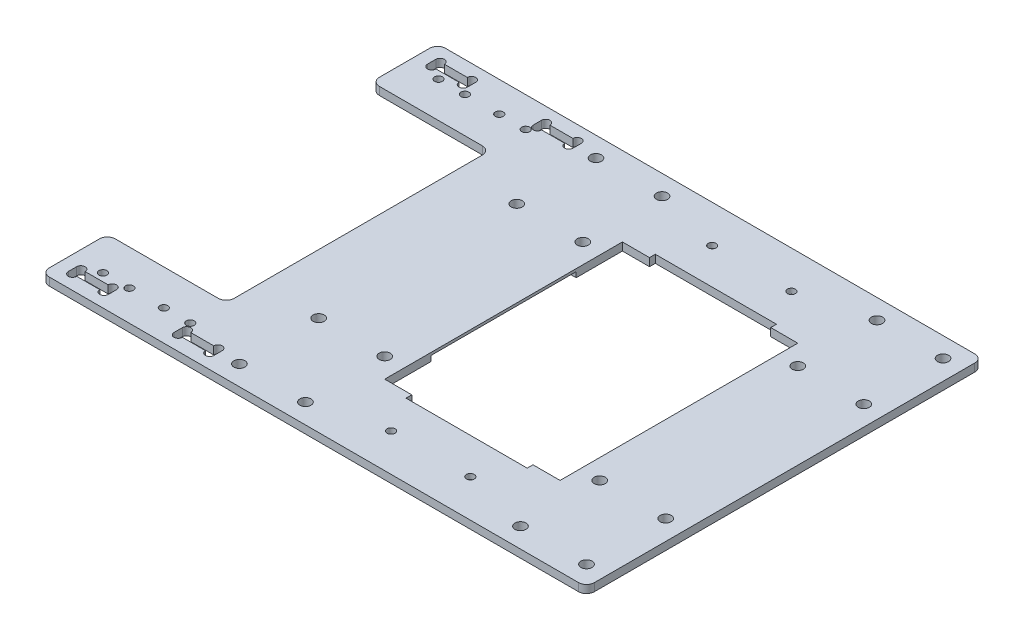
SolidWorks part; units mm, degrees
material "Thornel Mat VMA"
ref_plane "前视基准面" through (0, 0, 0) normal (0, 0, 1) x (1, 0, 0)
ref_plane "上视基准面" through (0, 0, 0) normal (0, 1, 0) x (1, 0, 0)
ref_plane "右视基准面" through (0, 0, 0) normal (1, 0, 0) x (0, 0, -1)
other "Configuration Table"
sketch "草图1" plane through (0, 0, 0) normal (0, 1, 0) x (1, 0, 0)
  line L0 (0, 0) -> (0, 27.529) construction
  line L1 (0, 0) -> (24.492, 0) construction
  line L2 (-73.2, 75) -> (-73.2, -75) construction
  line L3 (-133.2, -75) -> (73.2, -75)
  line L4 (-133.2, -75) -> (-133.2, 75)
  line L5 (-133.2, 75) -> (73.2, 75)
  line L6 (73.2, -75) -> (73.2, 75)
  line L7 (-133.2, -75) -> (73.2, 75) construction
  line L8 (-133.2, 75) -> (73.2, -75) construction
  circle A0 centre (65.7, 67.5) radius 2.1
  circle A1 centre (65.7, -67.5) radius 2.1
  circle A2 centre (-65.7, -67.5) radius 2.1
  circle A3 centre (-65.7, 67.5) radius 2.1
  circle A4 centre (-65.7, 37.5) radius 2.1 construction
  circle A5 centre (-40.7, 37.5) radius 2.1 construction
  circle A6 centre (-40.7, 67.5) radius 2.1 construction
  circle A7 centre (-40.7, -67.5) radius 2.1 construction
  circle A8 centre (-40.7, -37.5) radius 2.1 construction
  circle A9 centre (-65.7, -37.5) radius 2.1 construction
  circle A10 centre (40.7, -67.5) radius 2.1 construction
  circle A11 centre (40.7, -37.5) radius 2.1 construction
  circle A12 centre (65.7, -37.5) radius 2.1 construction
  circle A13 centre (65.7, 37.5) radius 2.1 construction
  circle A14 centre (40.7, 37.5) radius 2.1 construction
  circle A15 centre (40.7, 67.5) radius 2.1 construction
  circle A16 centre (-65.7, 37.5) radius 2.1
  circle A17 centre (-40.7, 37.5) radius 2.1
  circle A18 centre (-40.7, 67.5) radius 2.1
  circle A19 centre (-40.7, -67.5) radius 2.1
  circle A20 centre (-40.7, -37.5) radius 2.1
  circle A21 centre (-65.7, -37.5) radius 2.1
  circle A22 centre (40.7, -67.5) radius 2.1
  circle A23 centre (40.7, -37.5) radius 2.1
  circle A24 centre (65.7, -37.5) radius 2.1
  circle A25 centre (65.7, 37.5) radius 2.1
  circle A26 centre (40.7, 37.5) radius 2.1
  circle A27 centre (40.7, 67.5) radius 2.1
  circle A29 centre (-98.4, 63.575) radius 1.5
  circle A30 centre (-98.4, 63.575) radius 1.5
  circle A31 centre (-88.4, 63.575) radius 1.5
  circle A32 centre (-88.4, 63.575) radius 1.5
  circle A33 centre (-111.4, 63.575) radius 1.5
  circle A34 centre (-111.4, 63.575) radius 1.5
  circle A35 centre (-121.4, 63.575) radius 1.5
  circle A36 centre (-121.4, 63.575) radius 1.5
  circle A37 centre (-121.4, -63.475) radius 1.5
  circle A38 centre (-121.4, -63.475) radius 1.5
  circle A39 centre (-111.4, -63.475) radius 1.5
  circle A40 centre (-111.4, -63.475) radius 1.5
  circle A41 centre (-98.4, -63.425) radius 1.5
  circle A42 centre (-98.4, -63.425) radius 1.5
  circle A43 centre (-88.4, -63.425) radius 1.5
  circle A44 centre (-88.4, -63.425) radius 1.5
  point P6 (-30, 0)
  dimension "D1" = 135
  dimension "D2" = 131.4
  dimension "D3" = 4.2
  dimension "D4" = 7.5
  dimension "D5" = 7.5
  dimension "D6" = 60
  dimension "D7" = 7.5
  dimension "D8" = 0
  dimension "D9" = 0
  dimension "D10" = 0
  dimension "D11" = 0
  dimension "D12" = 0
  dimension "D13" = 0
  dimension "D14" = 0
  dimension "D15" = 0
extrude "凸台-拉伸1" add sketch "草图1" along normal blind 3
sketch "草图2" plane through (0, 0, 0) normal (0, 1, 0) x (1, 0, 0)
  line L0 (-128.4, -68) -> (-113.3, -68) construction
  line L1 (-125.2, -66.425) -> (-116.5, -66.425)
  line L2 (-128.4, -66.425) -> (-128.4, -69.575)
  line L3 (-125.2, -69.575) -> (-116.5, -69.575)
  line L4 (-113.3, -66.425) -> (-113.3, -69.575)
  line L5 (-120.85, -69.575) -> (-120.85, -66.425) construction
  line L6 (-85.2, -66.425) -> (-76.5, -66.425)
  line L7 (-88.4, -66.425) -> (-88.4, -69.575)
  line L8 (-85.2, -69.575) -> (-76.5, -69.575)
  line L9 (-73.3, -66.425) -> (-73.3, -69.575)
  line L10 (-88.4, -68) -> (-73.3, -68) construction
  line L11 (-80.85, -69.575) -> (-80.85, -66.425) construction
  line L12 (-133.2, 75) -> (-133.2, -75) construction
  line L14 (-133.2, 0) -> (73.2, 0) construction
  line L15 (73.2, -75) -> (73.2, 75) construction
  line L16 (-80.85, 69.575) -> (-80.85, 66.425) construction
  line L17 (-88.4, 68) -> (-73.3, 68) construction
  line L18 (-120.85, 69.575) -> (-120.85, 66.425) construction
  line L19 (-128.4, 68) -> (-113.3, 68) construction
  line L20 (-73.3, 66.425) -> (-73.3, 69.575)
  line L21 (-85.2, 69.575) -> (-76.5, 69.575)
  line L22 (-88.4, 66.425) -> (-88.4, 69.575)
  line L23 (-85.2, 66.425) -> (-76.5, 66.425)
  line L24 (-113.3, 66.425) -> (-113.3, 69.575)
  line L25 (-125.2, 69.575) -> (-116.5, 69.575)
  line L26 (-128.4, 66.425) -> (-128.4, 69.575)
  line L27 (-125.2, 66.425) -> (-116.5, 66.425)
  arc A0 (-128.4, -66.425) -> (-125.2, -66.425) centre (-126.8, -66.425) cw
  arc A1 (-113.3, -66.425) -> (-116.5, -66.425) centre (-114.9, -66.425) ccw
  arc A2 (-113.3, -69.575) -> (-116.5, -69.575) centre (-114.9, -69.575) cw
  arc A3 (-128.4, -69.575) -> (-125.2, -69.575) centre (-126.8, -69.575) ccw
  arc A4 (-88.4, -66.425) -> (-85.2, -66.425) centre (-86.8, -66.425) cw
  arc A5 (-73.3, -66.425) -> (-76.5, -66.425) centre (-74.9, -66.425) ccw
  arc A6 (-73.3, -69.575) -> (-76.5, -69.575) centre (-74.9, -69.575) cw
  arc A7 (-88.4, -69.575) -> (-85.2, -69.575) centre (-86.8, -69.575) ccw
  arc A8 (-88.4, 69.575) -> (-85.2, 69.575) centre (-86.8, 69.575) cw
  arc A9 (-73.3, 69.575) -> (-76.5, 69.575) centre (-74.9, 69.575) ccw
  arc A10 (-73.3, 66.425) -> (-76.5, 66.425) centre (-74.9, 66.425) cw
  arc A11 (-88.4, 66.425) -> (-85.2, 66.425) centre (-86.8, 66.425) ccw
  arc A12 (-128.4, 69.575) -> (-125.2, 69.575) centre (-126.8, 69.575) cw
  arc A13 (-113.3, 69.575) -> (-116.5, 69.575) centre (-114.9, 69.575) ccw
  arc A14 (-113.3, 66.425) -> (-116.5, 66.425) centre (-114.9, 66.425) cw
  arc A15 (-128.4, 66.425) -> (-125.2, 66.425) centre (-126.8, 66.425) ccw
  circle A16 centre (-65.7, 67.5) radius 2.1 construction
  dimension "D3" = 1.6
  dimension "D6" = 7.6
  dimension "D1" = 3.15
  dimension "D2" = 15.1
  dimension "D5" = 40
  dimension "D7" = 136
  dimension "D4" = 2
extrude "切除-拉伸1" cut sketch "草图2" along normal through all
fillet "圆角1" radius 3 4 edges at (73.2, 1.5, 75) (-133.2, 1.5, 75) (73.2, 1.5, -75) (-133.2, 1.5, -75)
sketch "草图4" plane through (0, 0, 0) normal (0, 1, 0) x (1, 0, 0)
  line L0 (-133.2, 72) -> (-133.2, -72) construction
  line L1 (-120.7, -27.5) -> (60.7, -27.5)
  line L2 (-125.7, -22.5) -> (-125.7, 22.5)
  line L3 (-120.7, 27.5) -> (60.7, 27.5)
  line L4 (65.7, -22.5) -> (65.7, 22.5)
  line L5 (-125.7, -27.5) -> (65.7, 27.5) construction
  line L6 (-125.7, 27.5) -> (65.7, -27.5) construction
  line L7 (65.7, 37.5) -> (65.7, -37.5) construction
  arc A0 (-120.7, -27.5) -> (-125.7, -22.5) centre (-120.7, -22.5) cw
  arc A1 (60.7, -27.5) -> (65.7, -22.5) centre (60.7, -22.5) ccw
  arc A2 (60.7, 27.5) -> (65.7, 22.5) centre (60.7, 22.5) cw
  arc A3 (-125.7, 22.5) -> (-120.7, 27.5) centre (-120.7, 22.5) cw
  circle A4 centre (40.7, 37.5) radius 2.1 construction
  point P0 (-30, 0)
  dimension "D1" = 5
  dimension "D2" = 10
  dimension "D3" = 7.5
extrude "切除-拉伸2" cut sketch "草图4" along normal blind 2
sketch "草图6" plane through (0, 3, 0) normal (0, 1, 0) x (1, 0, 0)
  circle A0 centre (0, 0) radius 10
  dimension "D1" = 20
extrude "切除-拉伸3" cut sketch "草图6" against normal blind 10
sketch "草图7" plane through (0, 3, 0) normal (0, 1, 0) x (1, 0, 0)
  line L0 (-133.2, 50) -> (-88.2, 50)
  line L1 (-133.2, 72) -> (-133.2, -72) construction
  line L2 (-88.2, 50) -> (-88.2, -50)
  line L3 (-88.2, -50) -> (-133.2, -50)
  line L4 (-133.2, -50) -> (-133.2, 50)
  line L5 (70.2, 75) -> (-130.2, 75) construction
  line L6 (-130.2, -75) -> (70.2, -75) construction
  dimension "D1" = 25
  dimension "D2" = 25
  dimension "D3" = 45
extrude "切除-拉伸4" cut sketch "草图7" against normal blind 10
fillet "圆角2" radius 3 4 edges at (-88.2, 1.5, -50) (-88.2, 1.5, 50) (-133.2, 1.5, 50) (-133.2, 1.5, -50)
sketch "草图8" plane through (0, 3, 0) normal (0, 1, 0) x (1, 0, 0)
  line L1 (-22.9421, -47.189) -> (22.9421, -47.189)
  line L2 (-22.9421, -47.189) -> (-22.9421, 47.189)
  line L3 (-22.9421, 47.189) -> (22.9421, 47.189)
  line L4 (22.9421, -47.189) -> (22.9421, 47.189)
  line L5 (-22.9421, -47.189) -> (22.9421, 47.189) construction
  line L6 (-22.9421, 47.189) -> (22.9421, -47.189) construction
  point P0 (0, 0)
extrude "切除-拉伸5" cut sketch "草图8" against normal blind 10
sketch "草图9" plane through (0, 3, 0) normal (0, 1, 0) x (1, 0, 0)
  line L0 (-33.2, -125) -> (-33.2, 125) construction
  line L1 (33.2, -45) -> (-33.2, -45)
  line L2 (33.2, -45) -> (33.2, 45)
  line L3 (33.2, 45) -> (-33.2, 45)
  line L4 (-33.2, -45) -> (-33.2, 45)
  line L5 (33.2, -45) -> (-33.2, 45) construction
  line L6 (33.2, 45) -> (-33.2, -45) construction
  line L7 (70.2, 75) -> (-130.2, 75) construction
  point P0 (0, 0)
  dimension "D1" = 30
extrude "切除-拉伸6" cut sketch "草图9" against normal blind 10
sketch "草图10" plane through (0, 3, 0) normal (0, 1, 0) x (1, 0, 0)
  line L0 (0, 87.6376) -> (0, -84.9769) construction
  line L1 (0, 0) -> (126.8925, 0) construction
  circle A0 centre (-15, 60.7802) radius 1.5
  circle A1 centre (15, 60.7802) radius 1.5
  circle A2 centre (15, -60.7802) radius 1.5
  circle A3 centre (-15, -60.7802) radius 1.5
  dimension "D1" = 3
  dimension "D2" = 15
extrude "切除-拉伸7" cut sketch "草图10" against normal blind 2
